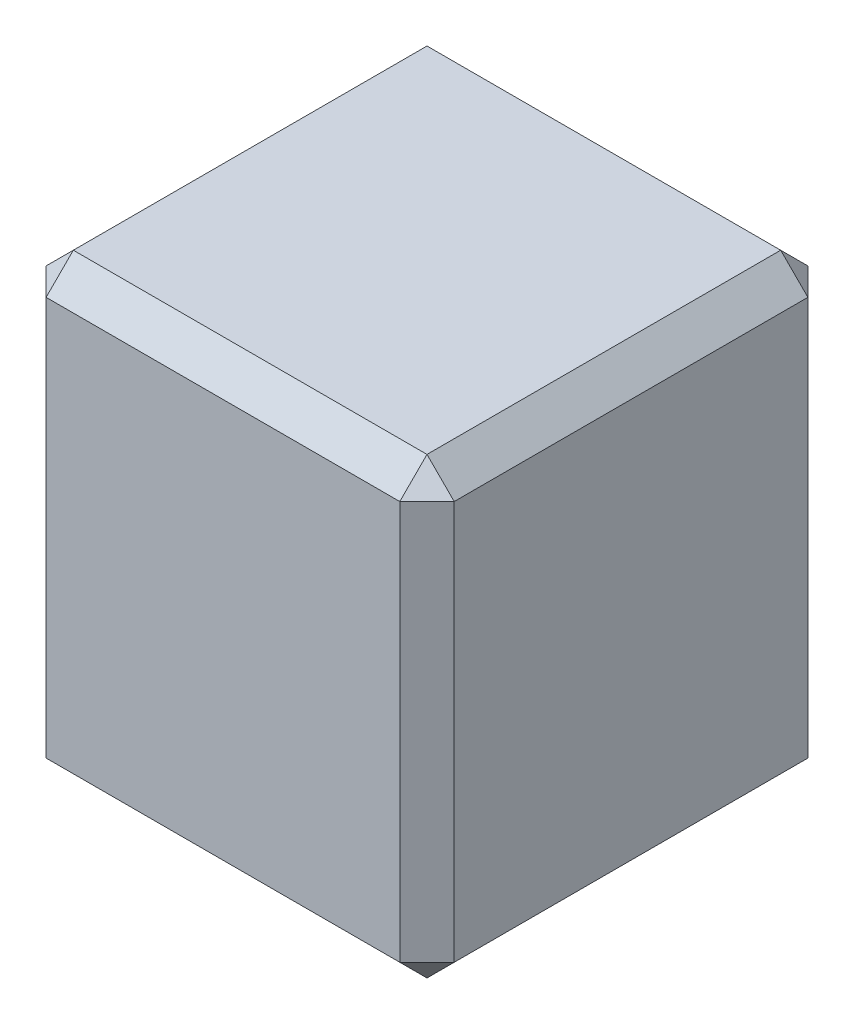
SolidWorks part; units mm, degrees
ref_plane "前视基准面" through (0, 0, 0) normal (0, 0, 1) x (1, 0, 0)
ref_plane "上视基准面" through (0, 0, 0) normal (0, 1, 0) x (1, 0, 0)
ref_plane "右视基准面" through (0, 0, 0) normal (1, 0, 0) x (0, 0, -1)
sketch "Sketch1" plane through (0, 0, 0) normal (0, 1, 0) x (1, 0, 0)
  line L1 (-22.5, 22.5) -> (22.5, 22.5)
  line L2 (-22.5, 22.5) -> (-22.5, -22.5)
  line L3 (-22.5, -22.5) -> (22.5, -22.5)
  line L4 (22.5, 22.5) -> (22.5, -22.5)
  line L5 (-22.5, 22.5) -> (22.5, -22.5) construction
  line L6 (-22.5, -22.5) -> (22.5, 22.5) construction
  point P0 (0, 0)
  dimension "D1" = 45
  dimension "D2" = 45
extrude "Boss-Extrude1" add sketch "Sketch1" along normal blind 50
sketch "Sketch2" plane through (0, 0, -22.5) normal (0, 0, -1) x (-1, 0, 0)
  circle A0 centre (0, 12.5) radius 4.15
  dimension "D1" = 8.3
  dimension "D2" = 12.5
extrude "Cut-Extrude1" cut sketch "Sketch2" against normal blind 30
sketch "Sketch3" plane through (-22.5, 0, 0) normal (-1, 0, 0) x (0, 0, 1)
  line L1 (-22.5, 50) -> (22.5, 50) construction
  circle A0 centre (0, 37.5) radius 4.15
  dimension "D1" = 8.3
  dimension "D2" = 12.5
extrude "Cut-Extrude2" cut sketch "Sketch3" against normal blind 30
chamfer "Chamfer1" distance 3 angle 45 12 edges at (0, 50, 22.5) (-22.5, 50, 0) (0, 50, -22.5) (22.5, 50, 0) (0, 0, 22.5) (22.5, 25, 22.5) (22.5, 0, 0) (-22.5, 25, 22.5) (-22.5, 0, 0) (-22.5, 25, -22.5) (0, 0, -22.5) (22.5, 25, -22.5)
